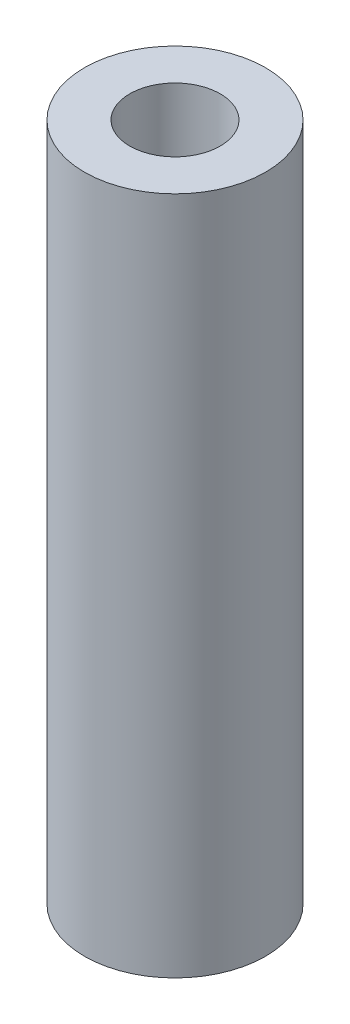
SolidWorks part; units mm, degrees
ref_plane "Front Plane" through (0, 0, 0) normal (0, 0, 1) x (1, 0, 0)
ref_plane "Top Plane" through (0, 0, 0) normal (0, 1, 0) x (1, 0, 0)
ref_plane "Right Plane" through (0, 0, 0) normal (1, 0, 0) x (0, 0, -1)
sketch "Sketch1" plane through (0, 0, 0) normal (0, 1, 0) x (1, 0, 0)
  circle A0 centre (0, 0) radius 4
  dimension "D1" = 8
extrude "Boss-Extrude1" add sketch "Sketch1" along normal blind 30
sketch "Sketch2" plane through (0, 30, 0) normal (0, 1, 0) x (1, 0, 0)
  circle A0 centre (0, 0) radius 2
  dimension "D1" = 4
extrude "Cut-Extrude1" cut sketch "Sketch2" against normal through all
